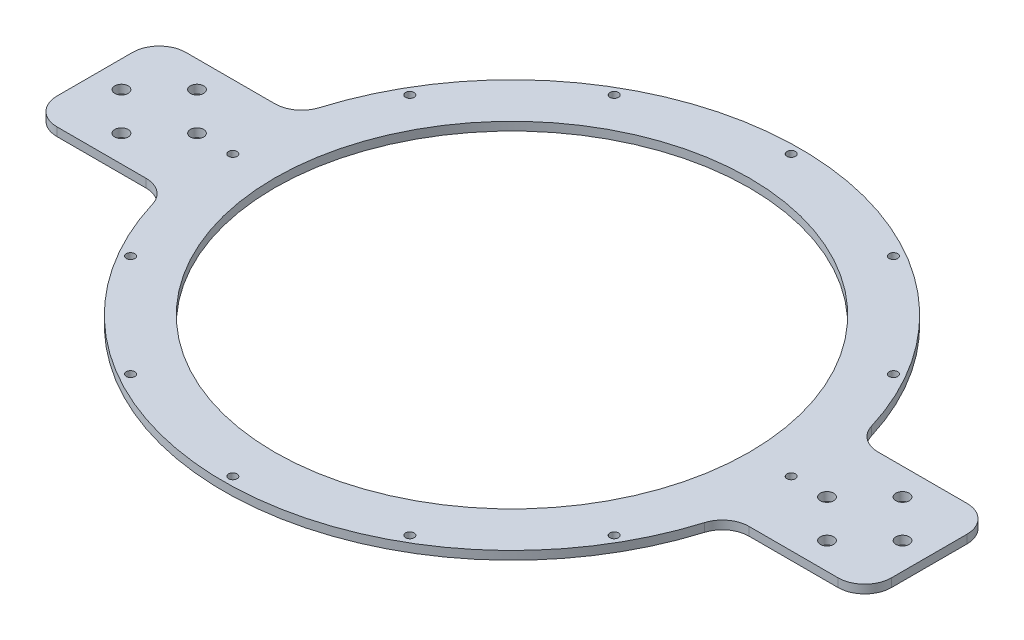
SolidWorks part; units mm, degrees
material "AISI 304"
ref_plane "Front Plane" through (0, 0, 0) normal (0, 0, 1) x (1, 0, 0)
ref_plane "Top Plane" through (0, 0, 0) normal (0, 1, 0) x (1, 0, 0)
ref_plane "Right Plane" through (0, 0, 0) normal (1, 0, 0) x (0, 0, -1)
sketch "Sketch1" plane through (0, 0, 0) normal (0, 1, 0) x (1, 0, 0)
  circle A0 centre (0, 0) radius 88.9
  circle A1 centre (0, 0) radius 107.95
  dimension "D1" = 177.8
  dimension "D2" = 215.9
extrude "Boss-Extrude1" add sketch "Sketch1" along normal blind 3.175
hole_wizard "M3 Clearance Hole1" positions "Sketch9" profile "Sketch10" hole size "M3" standard "ANSI Metric" end condition through all
sketch "Sketch9" plane through (0, 3.175, 0) normal (0, 1, 0) x (1, 0, 0)
  line L0 (0, 0) -> (0, 104.55) construction
  point P2 (0, 104.55)
  dimension "D1" = 104.55
sketch "Sketch10" plane through (0, 3.175, -104.55) normal (1, 0, 0) x (0, 0, 1)
  line L0 (0, 0) -> (0, 3.175)
  line L1 (0, 3.175) -> (1.6, 3.175)
  line L2 (1.6, 3.175) -> (1.6, 0)
  line L5 (1.6, 0) -> (0, 0)
  line L11 (0, -6.35) -> (0, 107.95) construction
  dimension "Thru Hole Dia." = 3.2
  dimension "Thru Hole Depth" = 3.175
pattern_circular "CirPattern1" count 12 over 360 about axis through (0, 0, 0) along (0, 1, 0) of "M3 Clearance Hole1"
sketch "Sketch2" plane through (0, 0, 0) normal (0, 1, 0) x (1, 0, 0)
  line L0 (-156.2343, 24.1421) -> (-105.2158, 24.1421)
  line L1 (-105.2158, -24.1421) -> (-156.2343, -24.1421)
  line L2 (-156.2343, -24.1421) -> (-156.2343, 24.1421)
  line L3 (-156.2343, 0) -> (0, 0) construction
  line L4 (-146.2343, 0) -> (-132.0921, 14.1421) construction
  line L5 (-132.0921, 14.1421) -> (-117.95, 0) construction
  line L6 (-117.95, 0) -> (-132.0921, -14.1421) construction
  line L7 (-132.0921, -14.1421) -> (-146.2343, 0) construction
  circle A0 centre (0, 0) radius 107.95 construction
  circle A1 centre (0, 0) radius 107.95 construction
  arc A2 (-105.2158, 24.1421) -> (-105.2158, -24.1421) centre (0, 0) ccw
  point P11 (-107.95, 0)
  dimension "D1" = 20
  dimension "D2" = 10
  dimension "D3" = 10
  dimension "D4" = 10
extrude "Boss-Extrude2" add sketch "Sketch2" along normal up to surface (3.175 mm away) up to face at (-52.275, 3.175, -88.943)
hole_wizard "#10 Clearance Hole3" positions "Sketch7" profile "Sketch8" hole size "#10" standard "ANSI Inch" end condition through all
sketch "Sketch7" plane through (0, 3.175, 0) normal (0, 1, 0) x (1, 0, 0)
  line L0 (-117.95, 0) -> (-132.0921, -14.1421) construction
  line L1 (-132.0921, -14.1421) -> (-146.2343, 0) construction
  line L2 (-146.2343, 0) -> (-132.0921, 14.1421) construction
  line L3 (-132.0921, 14.1421) -> (-117.95, 0) construction
  line L4 (-117.95, 0) -> (-132.0921, -14.1421) construction
  line L5 (-132.0921, -14.1421) -> (-146.2343, 0) construction
  line L6 (-146.2343, 0) -> (-132.0921, 14.1421) construction
  line L7 (-132.0921, 14.1421) -> (-117.95, 0) construction
  point P0 (-132.0921, -14.1421)
  point P2 (-117.95, 0)
  point P4 (-132.0921, 14.1421)
  point P6 (-146.2343, 0)
sketch "Sketch8" plane through (-132.0921, 3.175, 14.1421) normal (1, 0, 0) x (0, 0, 1)
  line L0 (0, 0) -> (0, 3.175)
  line L1 (0, 3.175) -> (2.4892, 3.175)
  line L2 (2.4892, 3.175) -> (2.4892, 0)
  line L5 (2.4892, 0) -> (0, 0)
  line L11 (0, -6.35) -> (0, 107.95) construction
  dimension "Thru Hole Dia." = 4.9784
  dimension "Thru Hole Depth" = 3.175
fillet "Fillet1" radius 10 4 edges at (-105.2158, 1.5875, -24.1421) (-156.2343, 1.5875, -24.1421) (-156.2343, 1.5875, 24.1421) (-105.2158, 1.5875, 24.1421)
mirror "Mirror1" about plane through (0, 0, 0) normal (1, 0, 0) of "#10 Clearance Hole3", "Fillet1", "Boss-Extrude2"
